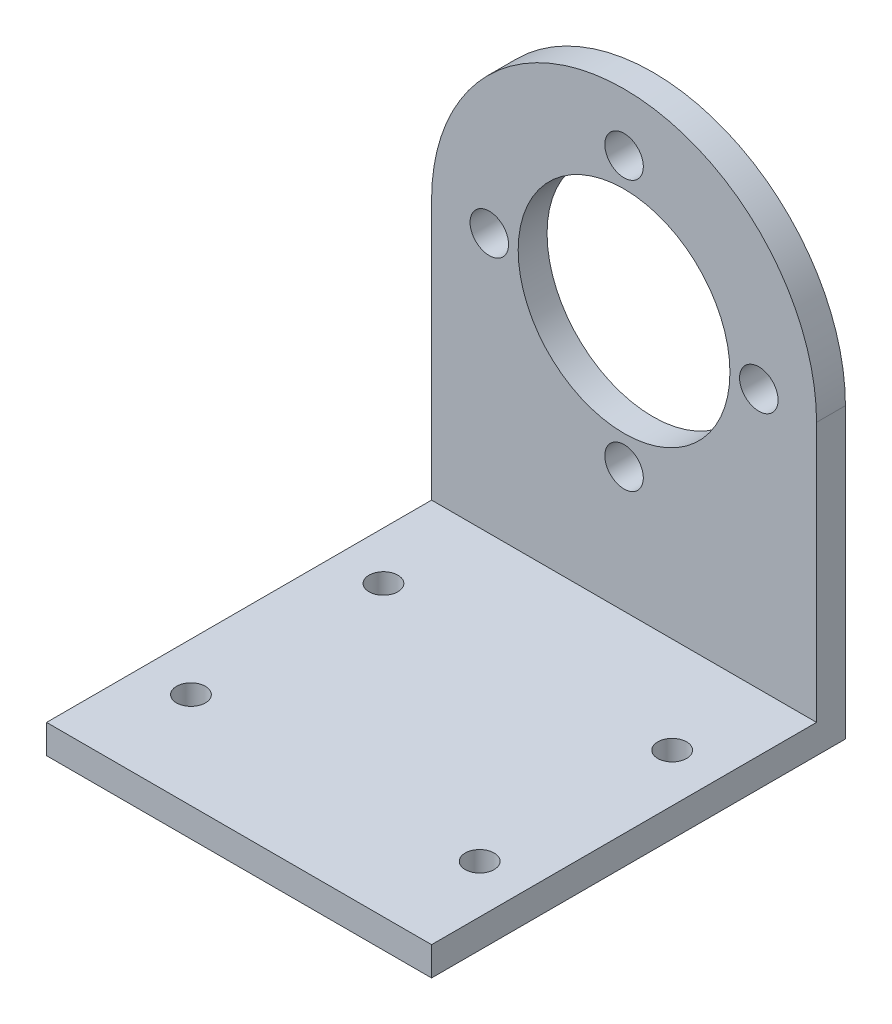
SolidWorks part; units mm, degrees
ref_plane "前视基准面" through (0, 0, 0) normal (0, 0, 1) x (1, 0, 0)
ref_plane "上视基准面" through (0, 0, 0) normal (0, 1, 0) x (1, 0, 0)
ref_plane "右视基准面" through (0, 0, 0) normal (1, 0, 0) x (0, 0, -1)
sketch "草图1" plane through (0, 0, 0) normal (0, 1, 0) x (1, 0, 0)
  line L1 (-20, 21.5) -> (20, 21.5)
  line L2 (-20, 21.5) -> (-20, -21.5)
  line L3 (-20, -21.5) -> (20, -21.5)
  line L4 (20, 21.5) -> (20, -21.5)
  circle A0 centre (-15, -11.5) radius 1.5
  circle A1 centre (15, -11.5) radius 1.5
  circle A2 centre (15, 8.5) radius 1.5
  circle A3 centre (-15, 8.5) radius 1.5
  dimension "D5" = 3
  dimension "D6" = 3
  dimension "D7" = 3
  dimension "D8" = 3
  dimension "D1" = 43
  dimension "D2" = 40
  dimension "D3" = 21.5
  dimension "D4" = 20
  dimension "D9" = 30
  dimension "D10" = 30
  dimension "D11" = 20
  dimension "D12" = 5
  dimension "D13" = 13
  dimension "D14" = 13
extrude "凸台-拉伸1" add sketch "草图1" along normal blind 3
sketch "草图3" plane through (0, 0, -21.5) normal (0, 0, -1) x (-1, 0, 0)
  line L0 (-20, 0) -> (-20, 30)
  line L2 (20, 0) -> (20, 30)
  line L3 (-20, 0) -> (20, 0)
  line L4 (0, 50) -> (0, 0) construction
  line L5 (-20, 30) -> (20, 30) construction
  arc A0 (-20, 30) -> (20, 30) centre (0, 30) cw
  circle A1 centre (0, 30) radius 11
  circle A7 centre (0, 44) radius 2
  circle A8 centre (14, 30) radius 2
  circle A9 centre (0, 16) radius 2
  circle A10 centre (-14, 30) radius 2
  point P22 (0, 30)
  dimension "D1" = 22
  dimension "D2" = 4
  dimension "D3" = 14
  dimension "D4" = 4
extrude "凸台-拉伸2" add sketch "草图3" against normal blind 3
